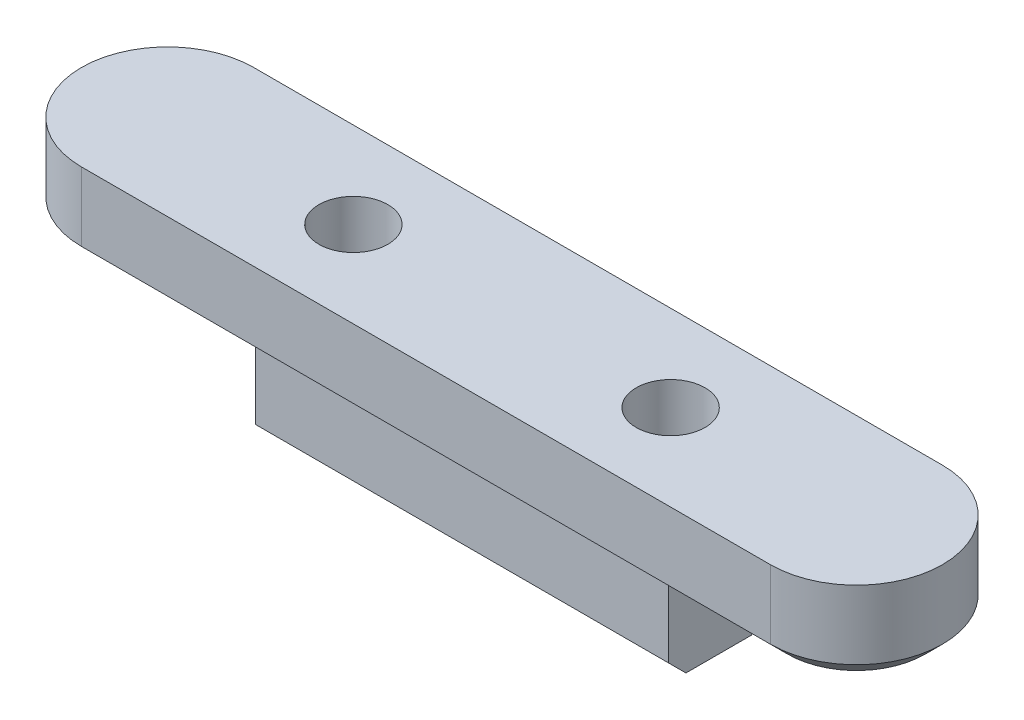
SolidWorks part; units mm, degrees
material "ABS"
ref_plane "Front Plane" through (0, 0, 0) normal (0, 0, 1) x (1, 0, 0)
ref_plane "Top Plane" through (0, 0, 0) normal (0, 1, 0) x (1, 0, 0)
ref_plane "Right Plane" through (0, 0, 0) normal (1, 0, 0) x (0, 0, -1)
sketch "Sketch1" plane through (0, 0, 0) normal (0, 1, 0) x (1, 0, 0)
  line L0 (0, 5) -> (-20, 5)
  line L2 (-20, -5) -> (0, -5)
  line L3 (0, 5) -> (0, -5)
  arc A2 (-20, -5) -> (-20, 5) centre (-20, 0) cw
  point P0 (0, 0)
  dimension "D1" = 5
  dimension "D2" = 20
extrude "Boss-Extrude1" add sketch "Sketch1" along normal blind 5
ref_axis "Axis1" through (-20, -4.1101, 0) along (0, 1, 0)
sketch "Sketch2" plane through (0, 0, 0) normal (0, 0, 1) x (1, 0, 0)
  line L0 (-20, -4.1101) -> (-20, 8.7798) construction
  line L1 (-20, 0) -> (-25, 0) construction
  line L2 (-20, 1) -> (-20, 0)
  line L3 (-20, 0) -> (-23.3166, 0)
  arc A0 (-20, 1) -> (-23.3166, 0) centre (-20, -5) ccw
  dimension "D1" = 6
  dimension "D2" = 1
revolve "Cut-Revolve1" cut sketch "Sketch2" angle 360 about axis through (-20, -4.1101, 0) along (0, 1, 0)
sketch "Sketch3" plane through (0, 0, 0) normal (0, -1, 0) x (1, 0, 0)
  line L0 (0, 5) -> (0, -5) construction
  line L1 (0, 2.9) -> (-12, 2.9)
  line L2 (0, 2.9) -> (0, -2.9)
  line L3 (0, -2.9) -> (-12, -2.9)
  line L4 (-12, 2.9) -> (-12, -2.9)
  line L5 (-20, 5) -> (0, 5) construction
  point P8 (0, 0)
  dimension "D1" = 2.1
  dimension "D2" = 12
extrude "Boss-Extrude2" add sketch "Sketch3" along normal blind 6
sketch "Sketch6" [suppressed] plane through (0, 0, 0) normal (0, -1, 0) x (1, 0, 0)
  line L1 (0, 5) -> (-12, 5)
  line L2 (0, 5) -> (0, 3)
  line L3 (0, 3) -> (-12, 3)
  line L4 (-12, 5) -> (-12, 3)
  dimension "D1" = 2
  dimension "D2" = 12
extrude "Boss-Extrude3" [suppressed] add sketch "Sketch6" along normal blind 6
mirror "Mirror2" [suppressed] about plane through (0, 0, 0) normal (0, 0, 1)
sketch "Sketch4" plane through (0, 0, 0) normal (0, 1, 0) x (1, 0, 0)
  circle A0 centre (-9.2106, 0) radius 1.6
  dimension "D1" = 3.2
extrude "Cut-Extrude1" cut sketch "Sketch4" against normal through all both and the other way through all
sketch "Sketch5" plane through (0, 5, 0) normal (0, 1, 0) x (1, 0, 0)
  circle A0 centre (-9.2106, 0) radius 2
  dimension "D1" = 4
extrude "Cut-Extrude2" cut sketch "Sketch5" against normal blind 4
chamfer "Chamfer1" [suppressed] distance 1.6 angle 45
mirror "Mirror1" about plane through (0, 0, 0) normal (1, 0, 0) of bodies 110
chamfer "Chamfer2" distance 1 angle 45 6 edges at (0, 0, -5) (-25, 0, 0) (25, 0, 0) (0, 0, 5) (0, -6, -2.9) (0, -6, 2.9)
chamfer "Chamfer3" [suppressed] distance 1 angle 45
equation "\"3ю2\"=1.60701"
